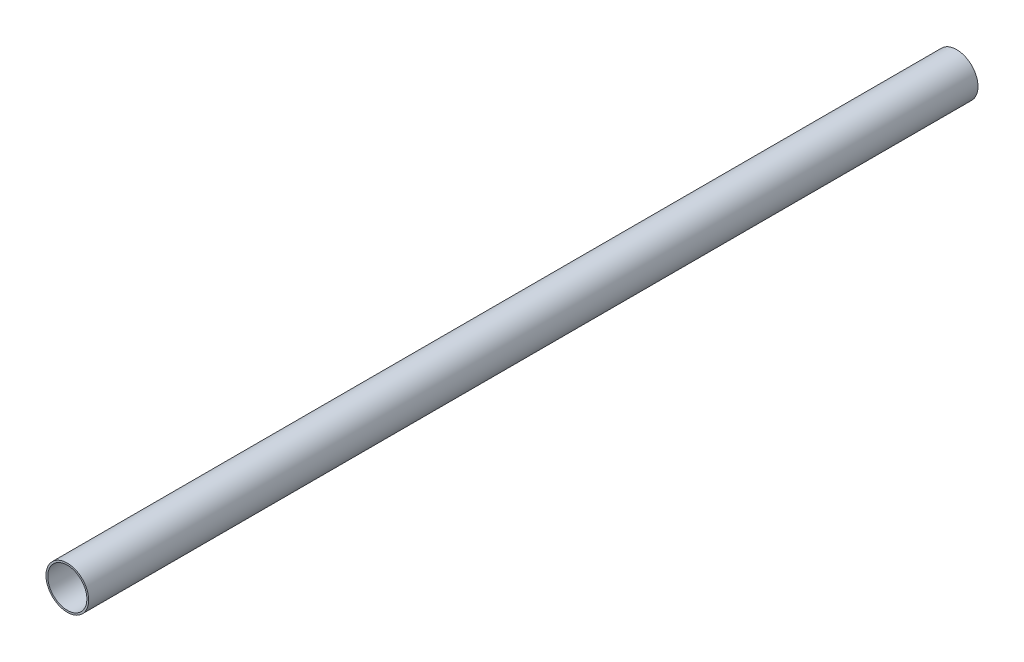
SolidWorks part; units mm, degrees
material "Plain Carbon Steel"
ref_plane "Front Plane" through (0, 0, 0) normal (0, 0, 1) x (1, 0, 0)
ref_plane "Top Plane" through (0, 0, 0) normal (0, 1, 0) x (1, 0, 0)
ref_plane "Right Plane" through (0, 0, 0) normal (1, 0, 0) x (0, 0, -1)
sketch "Sketch1" plane through (0, 0, 0) normal (0, 0, 1) x (1, 0, 0)
  circle A0 centre (0, 0) radius 6
  circle A1 centre (0, 0) radius 5.5
  dimension "D1" = 12
  dimension "D2" = 11
extrude "Boss-Extrude1" add sketch "Sketch1" along normal blind 250
ref_point "Point1"
